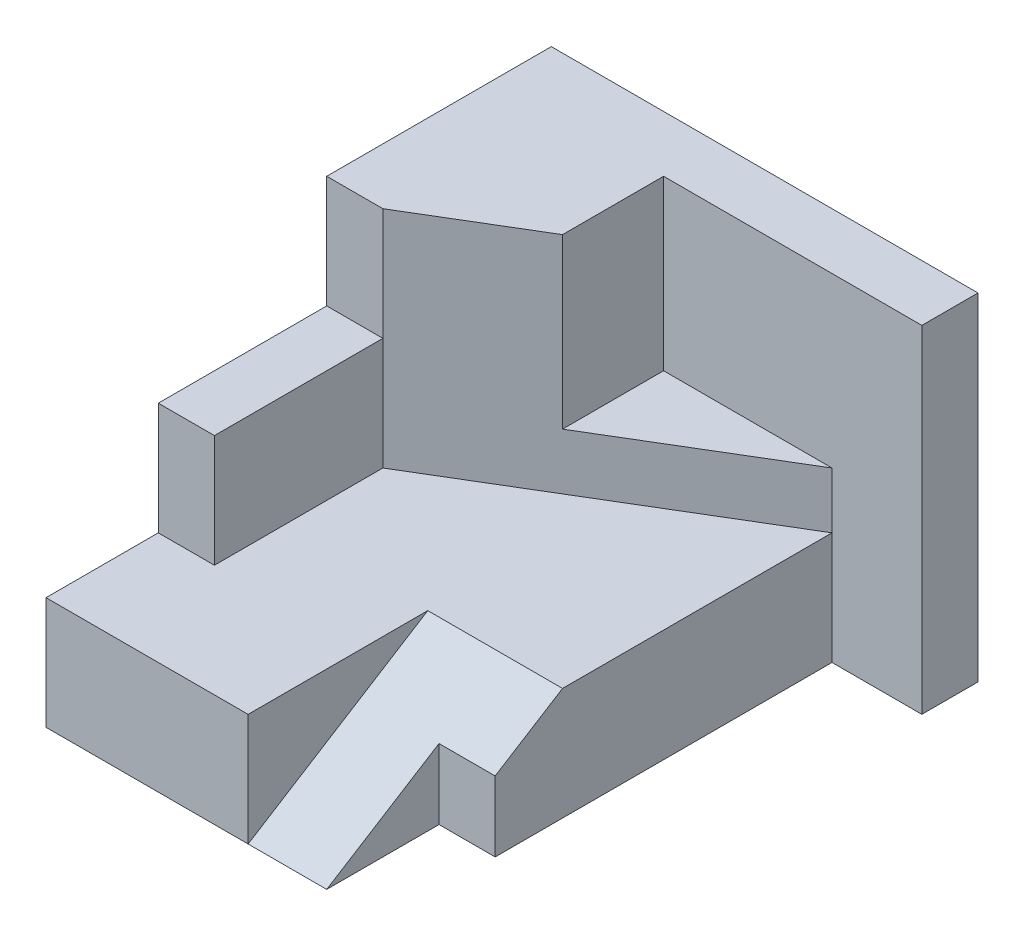
SolidWorks part; units mm, degrees
material "Copper"
ref_plane "Front Plane" through (0, 0, 0) normal (0, 0, 1) x (1, 0, 0)
ref_plane "Top Plane" through (0, 0, 0) normal (0, 1, 0) x (1, 0, 0)
ref_plane "Right Plane" through (0, 0, 0) normal (1, 0, 0) x (0, 0, -1)
sketch "Sketch1" plane through (0, 0, 0) normal (0, 1, 0) x (1, 0, 0)
  line L0 (0, 0) -> (38, 0)
  line L1 (38, 0) -> (38, -5)
  line L3 (5, -20) -> (0, -20)
  line L4 (0, -20) -> (0, 0)
  line L5 (38, -5) -> (30, -5)
  line L6 (30, -5) -> (5, -20)
  dimension "D1" = 38
  dimension "D2" = 5
  dimension "D3" = 20
  dimension "D4" = 5
  dimension "D5" = 8
extrude "Boss-Extrude1" add sketch "Sketch1" along normal blind 30
sketch "Sketch2" plane through (0, 0, 0) normal (0, 1, 0) x (1, 0, 0)
  line L1 (0, 0) -> (30, 0)
  line L2 (0, 0) -> (0, -45)
  line L3 (0, -45) -> (30, -45)
  line L4 (30, 0) -> (30, -45)
  dimension "D1" = 30
  dimension "D2" = 45
extrude "Boss-Extrude2" add sketch "Sketch2" along normal blind 10
sketch "Sketch3" plane through (0, 0, 0) normal (1, 0, 0) x (0, 0, -1)
  line L0 (-20, 30) -> (-5, 30) construction
  line L1 (-20, 10) -> (-35, 10)
  line L2 (-20, 10) -> (-20, 20)
  line L3 (-20, 20) -> (-35, 20)
  line L4 (-35, 10) -> (-35, 20)
  line L5 (-45, 10) -> (-45, 0) construction
  dimension "D1" = 10
  dimension "D2" = 10
extrude "Boss-Extrude3" add sketch "Sketch3" along normal blind 5
sketch "Sketch4" plane through (0, 30, 0) normal (0, 1, 0) x (1, 0, 0)
  line L0 (30, -5) -> (15, -5)
  line L1 (15, -5) -> (15, -14)
  line L2 (5, -20) -> (30, -5) construction
  line L3 (15, -14) -> (30, -5)
  dimension "D1" = 15
extrude "Cut-Extrude1" cut sketch "Sketch4" against normal blind 15
sketch "Sketch5" plane through (30, 0, 0) normal (1, 0, 0) x (0, 0, -1)
  line L0 (-45, 10) -> (-45, 0)
  line L1 (-45, 0) -> (-29, 10)
  line L2 (-45, 10) -> (-5, 10) construction
  line L3 (-29, 10) -> (-45, 10)
  dimension "D1" = 16
extrude "Cut-Extrude2" cut sketch "Sketch5" against normal blind 12
sketch "Sketch6" plane through (0, 0, 0) normal (0, 1, 0) x (1, 0, 0)
  line L1 (30, -45) -> (25, -45)
  line L2 (30, -45) -> (30, -35)
  line L3 (30, -35) -> (25, -35)
  line L4 (25, -45) -> (25, -35)
  dimension "D1" = 5
  dimension "D2" = 10
extrude "Cut-Extrude4" cut sketch "Sketch6" along normal through all
